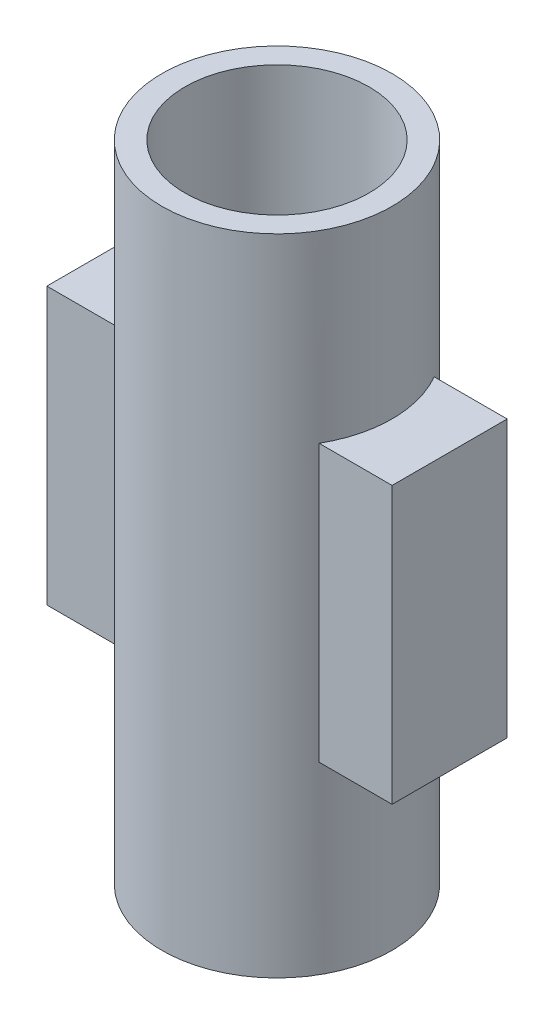
SolidWorks part; units mm, degrees
ref_plane "前视基准面" through (0, 0, 0) normal (0, 0, 1) x (1, 0, 0)
ref_plane "上视基准面" through (0, 0, 0) normal (0, 1, 0) x (1, 0, 0)
ref_plane "右视基准面" through (0, 0, 0) normal (1, 0, 0) x (0, 0, -1)
sketch "Sketch1" plane through (0, 0, 0) normal (0, 1, 0) x (1, 0, 0)
  line L1 (-7.5, 2.5) -> (7.5, 2.5)
  line L2 (-7.5, 2.5) -> (-7.5, -2.5)
  line L3 (-7.5, -2.5) -> (7.5, -2.5)
  line L4 (7.5, 2.5) -> (7.5, -2.5)
  line L5 (-7.5, 2.5) -> (7.5, -2.5) construction
  line L6 (-7.5, -2.5) -> (7.5, 2.5) construction
  circle A0 centre (0, 0) radius 5
  dimension "D1" = 15
  dimension "D2" = 5
extrude "Boss-Extrude1" add sketch "Sketch1" along normal blind 12 contours A0 L1 L2 L3 | L1 A0 | L3 A0 L1 | A0 L3 L4 L1 | L3 A0
sketch "Sketch2" plane through (0, 12, 0) normal (0, 1, 0) x (1, 0, 0)
  circle A0 centre (0, 0) radius 5
extrude "Boss-Extrude2" add sketch "Sketch2" along normal blind 8
sketch "Sketch3" plane through (0, 0, 0) normal (0, -1, 0) x (1, 0, 0)
  circle A0 centre (0, 0) radius 5
extrude "Boss-Extrude3" add sketch "Sketch3" along normal blind 8
sketch "Sketch4" plane through (0, -8, 0) normal (0, -1, 0) x (1, 0, 0)
  circle A0 centre (0, 0) radius 4
extrude "Cut-Extrude1" cut sketch "Sketch4" against normal through all
